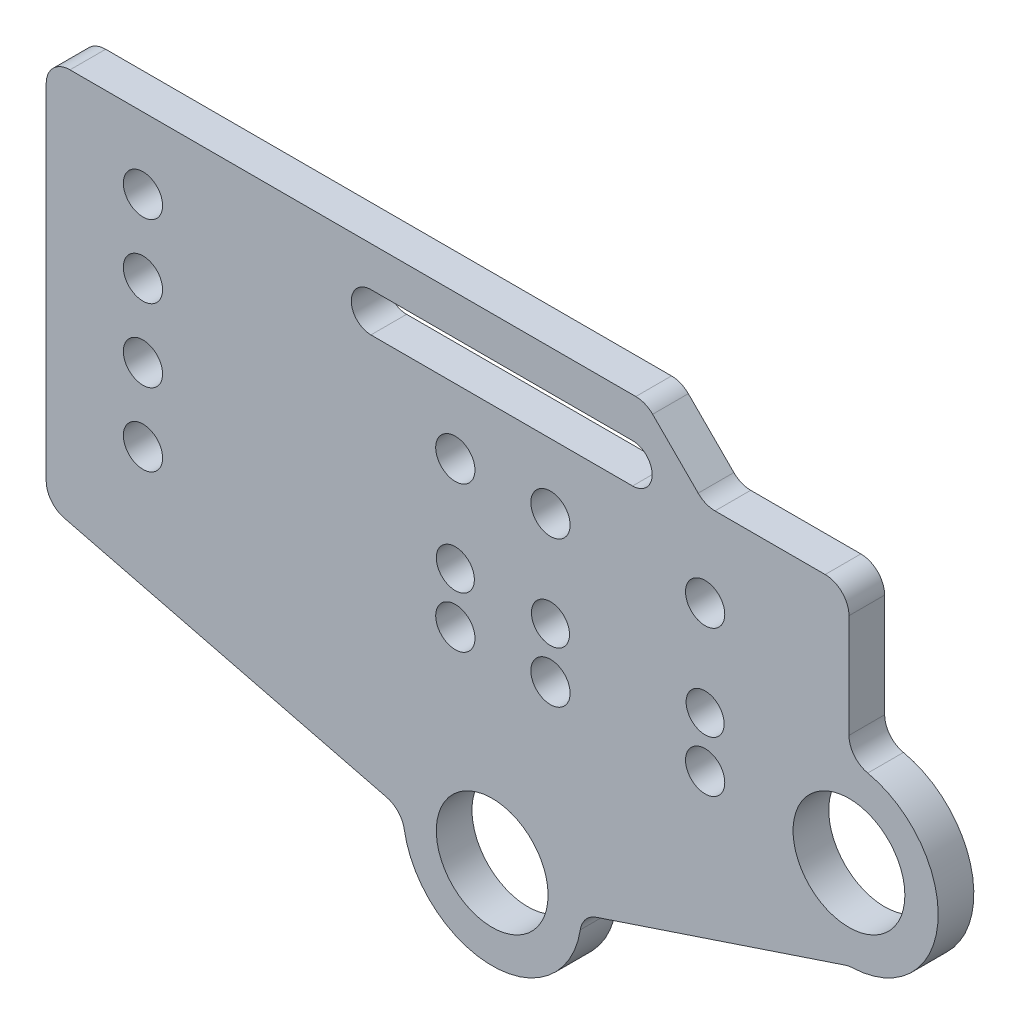
SolidWorks part; units mm, degrees
ref_plane "前视基准面" through (0, 0, 0) normal (0, 0, 1) x (1, 0, 0)
ref_plane "上视基准面" through (0, 0, 0) normal (0, 1, 0) x (1, 0, 0)
ref_plane "右视基准面" through (0, 0, 0) normal (1, 0, 0) x (0, 0, -1)
sketch "草图1" plane through (0, 0, 0) normal (0, 0, 1) x (1, 0, 0)
  line L0 (26.2006, 40) -> (0, 40)
  line L1 (8, 35) -> (60, 35)
  line L2 (0, 0) -> (0, 35)
  line L3 (0, 35) -> (60, 35)
  line L4 (0, 40) -> (0, 35)
  line L5 (45, 0) -> (67.5, 7.5)
  line L6 (67.5, 22.5) -> (67.5, 35)
  line L7 (67.5, 35) -> (60, 35)
  line L8 (0, 7.5) -> (30, 0)
  line L9 (30, 0) -> (29.8355, -0.0408)
  line L11 (21.2006, 35) -> (26.2006, 40)
  line L12 (55.4062, 35) -> (50.4063, 40)
  line L21 (50.4063, 40) -> (26.2006, 40)
  circle A0 centre (37.5, 0) radius 7.5
  circle A1 centre (37.5, 0) radius 4.7
  circle A2 centre (67.5, 15) radius 7.5
  circle A3 centre (8.1361, 21.75) radius 1.65
  circle A4 centre (67.5, 15) radius 4.7
  circle A5 centre (8.1361, 15.625) radius 1.65
  circle A6 centre (8.1361, 27.875) radius 1.65
  circle A7 centre (55.4062, 27.875) radius 1.65
  circle A8 centre (55.4062, 15.625) radius 1.65
  circle A9 centre (34.4011, 15.625) radius 1.65
  circle A10 centre (34.4011, 27.875) radius 1.65
  circle A11 centre (42.4011, 27.875) radius 1.65
  circle A12 centre (42.4011, 15.625) radius 1.65
  circle A13 centre (8.1361, 34) radius 1.65
  dimension "D1" = 21.0051
  dimension "D2" = 8
extrude "凸台-拉伸1" add sketch "草图1" along normal blind 3
fillet "圆角4" radius 2 9 edges at (67.5, 35, 1.5) (67.5, 22.5, 1.5) (67.5, 7.5, 1.5) (45, 0, 1.5) (30, 0, 1.5) (0, 7.5, 1.5) (55.4062, 35, 1.5) (50.4063, 40, 1.5) (0, 40, 1.5)
sketch "草图2" plane through (0, 0, 0) normal (0, 0, 1) x (1, 0, 0)
  line L1 (38.3034, 35) -> (49.3034, 35)
  line L2 (38.3034, 35) -> (38.3034, 36.65)
  line L3 (38.3034, 35) -> (49.3034, 35)
  line L4 (38.3034, 35) -> (38.3034, 33.35)
  line L5 (49.3034, 35) -> (49.3034, 33.35)
  line L6 (38.3034, 33.35) -> (49.3034, 33.35)
  line L7 (49.3034, 35) -> (49.3034, 36.65)
  line L8 (38.3034, 36.65) -> (49.3034, 36.65)
  line L9 (38.3034, 36.65) -> (38.3034, 33.35)
  line L10 (38.3034, 36.65) -> (27.3034, 36.65)
  line L11 (38.3034, 33.35) -> (27.3034, 33.35)
  line L12 (27.3034, 36.65) -> (27.3034, 33.35)
  circle A0 centre (27.3034, 35) radius 1.65
  circle A1 centre (49.3034, 35) radius 0.3253
  circle A2 centre (49.3034, 35) radius 1.65
extrude "切除-拉伸2" cut sketch "草图2" along normal blind 10
sketch "草图3" plane through (0, 0, 0) normal (0, 0, 1) x (1, 0, 0)
  line L0 (34.4011, 27.875) -> (42.4011, 27.875)
  line L1 (34.4011, 27.875) -> (34.4011, 19.875)
  line L2 (42.4011, 27.875) -> (42.4011, 19.875)
  line L3 (34.4011, 19.875) -> (42.4011, 19.875)
  circle A0 centre (34.4011, 19.875) radius 1.6
  circle A1 centre (42.4011, 19.875) radius 1.6
  circle A2 centre (55.4062, 19.875) radius 1.6
extrude "切除-拉伸4" cut sketch "草图3" along normal blind 10 contours L1 A0 L3 | L3 A1 L2 | A2 | L2 A1 L3 | L3 A0 L1
